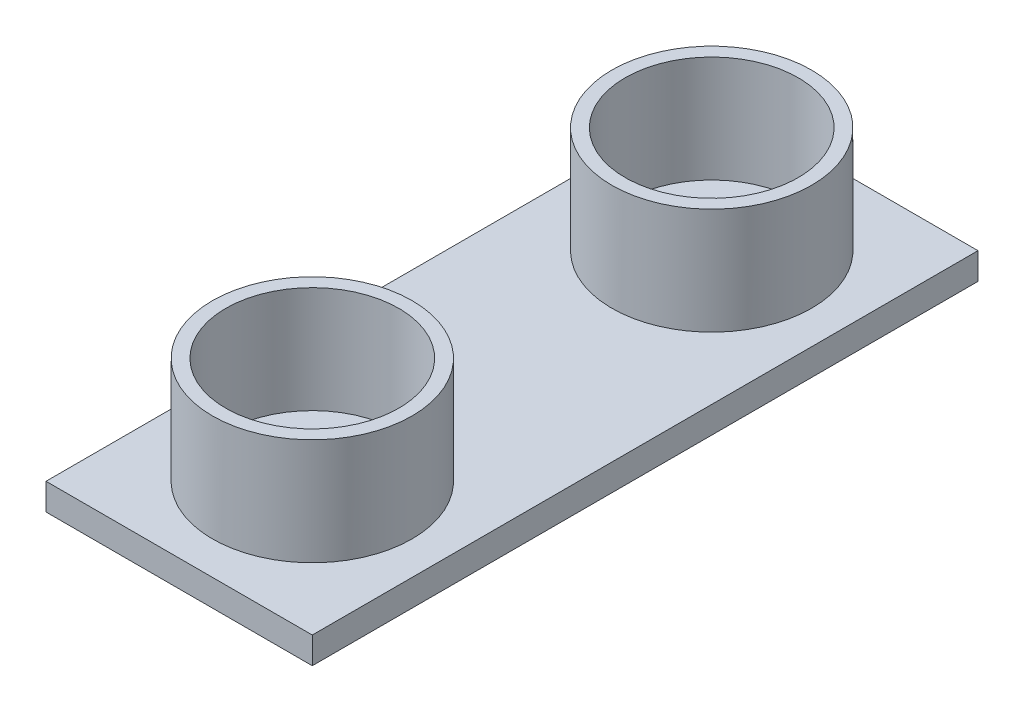
SolidWorks part; units mm, degrees
ref_plane "Front Plane" through (0, 0, 0) normal (0, 0, 1) x (1, 0, 0)
ref_plane "Top Plane" through (0, 0, 0) normal (0, 1, 0) x (1, 0, 0)
ref_plane "Right Plane" through (0, 0, 0) normal (1, 0, 0) x (0, 0, -1)
sketch "Sketch1" plane through (0, 0, 0) normal (0, 0, 1) x (1, 0, 0)
  line L1 (1, -0.1) -> (-1, -0.1)
  line L2 (1, -0.1) -> (1, 0.1)
  line L3 (1, 0.1) -> (-1, 0.1)
  line L4 (-1, -0.1) -> (-1, 0.1)
  line L5 (1, -0.1) -> (-1, 0.1) construction
  line L6 (1, 0.1) -> (-1, -0.1) construction
  point P0 (0, 0)
  dimension "D1" = 0.2
  dimension "D2" = 2
extrude "Boss-Extrude1" add sketch "Sketch1" along normal blind 5
sketch "Sketch2" plane through (0, 0.1, 0) normal (0, 1, 0) x (1, 0, 0)
  line L0 (1, 0) -> (-1, 0) construction
  line L1 (1, -5) -> (-1, -5) construction
  circle A0 centre (0, -1) radius 0.75
  circle A1 centre (0, -4) radius 0.75
  circle A2 centre (0, -1) radius 0.65
  circle A3 centre (0, -4) radius 0.65
  dimension "D3" = 1.5
  dimension "D4" = 1.5
  dimension "D5" = 1.3
  dimension "D6" = 1.3
  dimension "D1" = 1
  dimension "D2" = 1
extrude "Boss-Extrude2" add sketch "Sketch2" along normal blind 0.8
